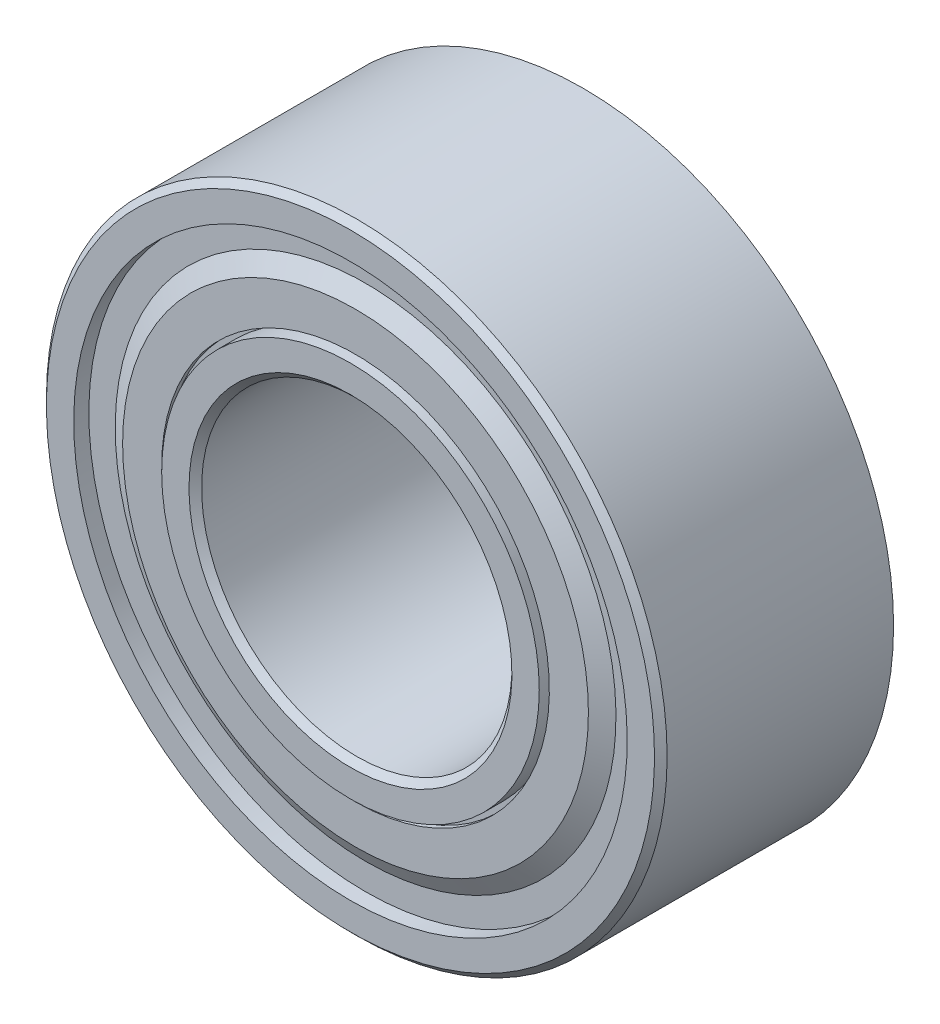
SolidWorks part; units mm, degrees
ref_plane "Front Plane" through (0, 0, 0) normal (0, 0, 1) x (1, 0, 0)
ref_plane "Top Plane" through (0, 0, 0) normal (0, 1, 0) x (1, 0, 0)
ref_plane "Right Plane" through (0, 0, 0) normal (1, 0, 0) x (0, 0, -1)
sketch "Sketch1" plane through (0, 0, 0) normal (1, 0, 0) x (0, 0, -1)
  line L0 (0, 4) -> (0, -4) construction
  line L1 (-1.5, 4) -> (1.5, 4) construction
  line L2 (0, 0) -> (1.5, 0) construction
  line L3 (1.5, 4.6) -> (1.5, -4.6) construction
  line L4 (1.5, -4.6) -> (0.9, -4.6) construction
  line L5 (1.5, 2) -> (0, 2) construction
  line L6 (1.5, 2) -> (1.5, -2) construction
  dimension "OD" = 8
  dimension "Width" = 3
  dimension "Flange Thickness" = 0.6
  dimension "ID" = 4
  dimension "Flange OD" = 9.2
sketch "Sketch2" plane through (0, 0, 0) normal (1, 0, 0) x (0, 0, -1)
  line L0 (1.5, 4.6) -> (0.9, 4.6)
  line L1 (0.9, 4.6) -> (0.9, 4.2652)
  line L2 (0.6348, 4) -> (-1.5, 4)
  line L3 (-1.5, 4) -> (-1.5, 3.35)
  line L4 (-1.5, 3.35) -> (-0.4873, 3.35)
  line L5 (1.5, 4.6) -> (1.5, -4.6) construction
  line L6 (1.5, 3.35) -> (1.5, 4.6)
  line L7 (1.5, 2) -> (-1.5, 2)
  line L8 (-1.5, 2) -> (-1.5, 2.65)
  line L9 (-1.5, 2.65) -> (-0.4873, 2.65)
  line L10 (1.5, 2.65) -> (1.5, 2)
  line L11 (0, 4) -> (0, 2) construction
  line L12 (-0.6, 3) -> (0.6, 3) construction
  line L13 (0.4873, 3.35) -> (1.5, 3.35)
  line L14 (0.4873, 2.65) -> (1.5, 2.65)
  line L15 (0.9, 4.2652) -> (1.0326, 4.1326)
  line L16 (1.0326, 4.1326) -> (1.0326, 3.8674)
  line L17 (1.0326, 3.8674) -> (0.7674, 3.8674)
  line L18 (0.7674, 3.8674) -> (0.6348, 4)
  line L19 (0.9, 4) -> (1.0326, 3.8674) construction
  line L20 (1.0326, 4.1326) -> (0.7674, 3.8674) construction
  line L21 (0.6348, 4) -> (0.9, 4) construction
  line L22 (0.9, 4) -> (0.9, 4.2652) construction
  line L23 (-1.5, 0) -> (1.5, 0) construction
  circle A0 centre (0, 3) radius 0.6 construction
  arc A1 (-0.4873, 3.35) -> (0.4873, 3.35) centre (0, 3) cw
  arc A2 (-0.4873, 2.65) -> (0.4873, 2.65) centre (0, 3) ccw
  dimension "Ball Dia." = 1.2
  dimension "D2" = 135
  dimension "D3" = 0.375
  dimension "Race Thikness" = 0.65
  dimension "D4" = 0.7
revolve "Revolve1" add sketch "Sketch2" angle 360 about L2
fillet "Fillet1" radius 0.0813 3 edges at (0, -4.6, -1.5) (0, -4.6, -0.9) (0, -4, 1.5) profile chamfer
sketch "Sketch3" plane through (0, 0, 0) normal (0, 0, 1) x (1, 0, 0)
  line L0 (-2, 0) -> (2, 0) construction
  line L1 (-4, 0) -> (4, 0) construction
  point P5 (0, 0)
  dimension "ID2" = 4
  dimension "OD2" = 8
fillet "Fillet2" radius 0.0813 2 edges at (0, -2, -1.5) (0, -2, 1.5) profile chamfer
sketch "Sketch7" plane through (0, 0, 0) normal (0, 0, 1) x (1, 0, 0)
  line L0 (0, 3.6) -> (0, 2.4)
  line L1 (0, 4.6) -> (0, -4.6) construction
  line L2 (-0.7348, 3.6) -> (0, 0) construction
  line L3 (0, 0) -> (0.7348, 3.6) construction
  line L4 (0.7348, 3.6) -> (-0.7348, 3.6) construction
  circle A0 centre (0, 3) radius 0.6 construction
  circle A1 centre (0, 0) radius 3.6 construction
  circle A2 centre (0, 0) radius 2.4 construction
  arc A4 (0, 3.6) -> (0, 2.4) centre (0, 3) ccw
  dimension "D1" = 23.074
revolve "Revolve3" add sketch "Sketch7" angle 360 about L0
pattern_circular "CirPattern3" count 12 over 360 about axis through (0, 0, 0) along (0, 0, 1) of bodies 107
sketch "Sketch8" plane through (0, 0, 0) normal (1, 0, 0) x (0, 0, -1)
  line L1 (-1.5, 3.35) -> (-1.24, 3.35)
  line L2 (-1.5, 3.35) -> (-1.5, 3.5667)
  line L3 (-1.5, 3.5667) -> (-1.24, 3.5667)
  line L4 (-1.24, 3.35) -> (-1.24, 3.5667)
  line L5 (1.5, 3.35) -> (1.24, 3.35)
  line L6 (1.5, 3.35) -> (1.5, 3.5667)
  line L7 (1.5, 3.5667) -> (1.24, 3.5667)
  line L8 (1.24, 3.35) -> (1.24, 3.5667)
  line L9 (1.5, 2.65) -> (1.24, 2.65)
  line L10 (1.5, 2.65) -> (1.5, 2.4333)
  line L11 (1.5, 2.4333) -> (1.24, 2.4333)
  line L12 (1.24, 2.65) -> (1.24, 2.4333)
  line L13 (-1.5, 2.65) -> (-1.24, 2.65)
  line L14 (-1.5, 2.65) -> (-1.5, 2.4333)
  line L15 (-1.5, 2.4333) -> (-1.24, 2.4333)
  line L16 (-1.24, 2.65) -> (-1.24, 2.4333)
  dimension "D1" = 0.2167
  dimension "D2" = 0.26
revolve "Cut-Revolve1" cut sketch "Sketch8" angle 360 about L2
sketch "Sketch9" plane through (0, 0, 0) normal (1, 0, 0) x (0, 0, -1)
  line L0 (-1.24, 3.5667) -> (-1.24, 3.2095)
  line L1 (-1.24, 3.2095) -> (-1.37, 2.9844)
  line L2 (-1.37, 2.9844) -> (-1.37, 2.4983)
  line L3 (1.37, 2.4983) -> (1.37, 2.4333) construction
  line L4 (1.24, 3.5667) -> (1.24, 3.2095)
  line L5 (1.24, 3.2095) -> (1.37, 2.9844)
  line L6 (1.37, 2.9844) -> (1.37, 2.4983)
  line L7 (1.5, 2.4333) -> (1.24, 2.4333) construction
  line L8 (-1.305, 3.5667) -> (-1.305, 3.2269)
  line L9 (-1.305, 3.2269) -> (-1.435, 3.0018)
  line L10 (-1.435, 3.0018) -> (-1.435, 2.4983)
  line L11 (-1.24, 3.5667) -> (-1.305, 3.5667)
  line L12 (-1.37, 2.4983) -> (-1.435, 2.4983)
  line L13 (1.305, 3.5667) -> (1.305, 3.2269)
  line L14 (1.305, 3.2269) -> (1.435, 3.0018)
  line L15 (1.435, 3.0018) -> (1.435, 2.4983)
  line L16 (1.24, 3.5667) -> (1.305, 3.5667)
  line L17 (1.37, 2.4983) -> (1.435, 2.4983)
  line L18 (-1.24, 3.2095) -> (-1.24, 2.5308) construction
  line L19 (1.24, 3.2095) -> (1.24, 3.5667) construction
  line L20 (-1.24, 2.4333) -> (-1.5, 2.4333) construction
  line L22 (-1.37, 2.4983) -> (-1.37, 2.4333) construction
  dimension "D2" = 150
  dimension "D1" = 150
  dimension "D5" = 0.26
  dimension "D3" = 0.065
  dimension "D4" = 0.065
  dimension "D6" = 0.3571
revolve "Revolve4" add sketch "Sketch9" angle 360 about L2
sketch "Sketch10" plane through (0, 0, 1.5) normal (0, 0, 1) x (1, 0, 0)
  circle A0 centre (0, 0) radius 4.6
  circle A2 centre (0, 0) radius 4
  dimension "D1" = 9.2
  dimension "D2" = 8
extrude "Cut-Extrude1" cut sketch "Sketch10" against normal through all both and the other way through all
sketch "Sketch11" plane through (0, 0, -1.0326) normal (0, 0, 1) x (1, 0, 0)
  circle A0 centre (0, 0) radius 4
  circle A1 centre (0, 0) radius 3.8674
  dimension "D1" = 7.7348
  dimension "D2" = 8
extrude "Boss-Extrude1" add sketch "Sketch11" along normal up to surface (0.3977 mm away) from surface at 0 contours A0 starting at face at (0, -4, -0.6348)
sketch "Sketch12" plane through (0, 0, -0.6348) normal (0, 0, 1) x (1, 0, 0)
  circle A0 centre (0, 0) radius 2
  dimension "D1" = 4
extrude "Cut-Extrude2" cut sketch "Sketch12" against normal through all both and the other way through all
equation "\"D1@Fillet1\"=\"Race Thikness@Sketch2\"/8"
equation "\"ID2@Sketch3\" = \"ID@Sketch1\""
equation "\"OD2@Sketch3\" = \"OD@Sketch1\""
equation "\"D1@Fillet2\"=\"Race Thikness@Sketch2\"/8"
equation "\"D1@CirPattern3\"=360/\"D1@Sketch7\"-4"
equation "\"D1@Sketch8\"=\"Race Thikness@Sketch2\"/3"
equation "\"D2@Sketch8\"=\"Race Thikness@Sketch2\"/2.5"
equation "\"D3@Sketch9\"=\"D5@Sketch9\"/4"
equation "\"D4@Sketch9\"=\"D5@Sketch9\"/4"
equation "\"D1@Sketch9\"=\"D2@Sketch9\""
equation "\"Ball Dia.@Sketch2\" = \"D1@Sketch2\"*.5"
equation "\"D4@Sketch2\"=((\"OD@Sketch1\"-\"ID@Sketch1\")/2)*.35"
